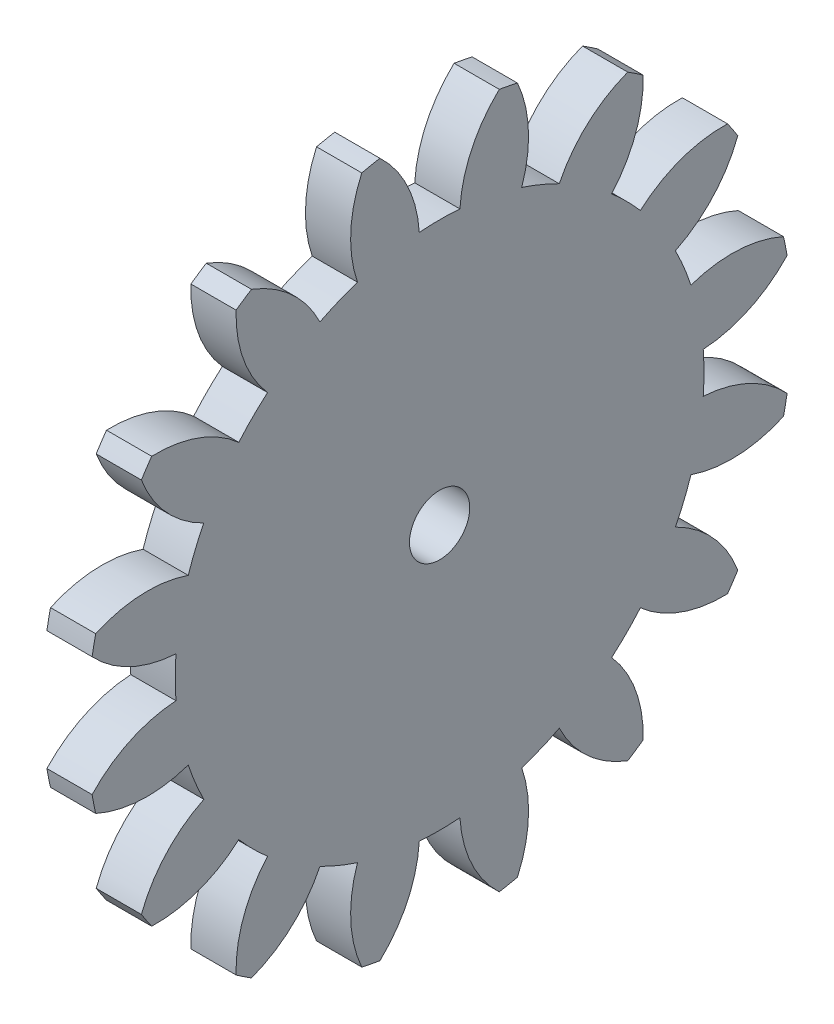
SolidWorks part; units mm, degrees
ref_plane "Plane1" through (0, 0, 0) normal (0, 0, 1) x (1, 0, 0)
ref_plane "Plane2" through (0, 0, 0) normal (0, 1, 0) x (1, 0, 0)
ref_plane "Plane3" through (0, 0, 0) normal (1, 0, 0) x (0, 0, -1)
sketch "HoldingSke" plane through (0, 0, 0) normal (0, 1, 0) x (1, 0, 0)
  line L0 (0, 0) -> (0.7394, -0.212)
  line L1 (-15, 0) -> (100, 0) construction
  line L2 (0, 0) -> (-2.1039, 2.3779)
  line L3 (0, 0) -> (-11.863, 4.5341)
  line L4 (0, 0) -> (8.3015, 2.3804)
  line L5 (0, 0) -> (-46.8476, -17.4728)
  line L6 (0, 0) -> (-1.2434, -0.839)
  line L7 (-2.1039, 2.3779) -> (8.6586, 51.2059)
  line L8 (-76.2, 54.61) -> (-75.9, 54.61)
  line L9 (-71.009, 38.7566) -> (-53.1078, 45.2721)
  line L10 (-76.2, 71.12) -> (104.1128, 71.12)
  line L11 (0, 0) -> (-1.5, 0)
  line L12 (-76.2, 101.6) -> (-76.155, 101.6)
  line L13 (24.9733, 27.94) -> (52.9518, 28.4284)
  line L14 (24.9733, 27.94) -> (24.9743, 27.94)
  line L15 (24.9733, 27.94) -> (100.4006, 29.5858)
  line L16 (-63.627, -1.3) -> (-12.827, -1.3)
  circle A0 centre (0, 0) radius 1
  circle A1 centre (0, 0) radius 8.774
  circle A2 centre (0, 0) radius 37.5
  circle A3 centre (0, 0) radius 1
  dimension "MHD" = 17.548
  dimension "Hub_dia" = 75
  dimension "Bore" = 2
  dimension "MBD" = 2
  dimension "Num_teeth" = 16
  dimension "Pitch" = 0.7692
  dimension "Overall_len" = 50
  dimension "Show_teeth" = 16
  dimension "Thickness" = 1.5
  dimension "OAL" = 50.0001
  dimension "T_dim" = 0.3
  dimension "Ap" = 20
  dimension "H" = 19.05
  dimension "Pitch_radius" = 180.3128
  dimension "Width" = 1.5
  dimension "Backlash" = 0.045
  dimension "Addendum_fac" = 1
  dimension "Dedendum_fac" = 1.25
  dimension "Clearance_fac" = 0.25
  dimension "Dedendum_add" = 0.001
  dimension "Module" = 1.3
sketch "BasProSke" plane through (0, 0, 0) normal (0, 1, 0) x (1, 0, 0)
  line L0 (-10, 0) -> (60, 0) construction
  line L1 (0, 0) -> (0, 11.7)
  line L2 (0, 0) -> (1.5, 0)
  line L3 (1.5, 0) -> (1.5, 11.7)
  line L4 (1.5, 11.7) -> (0, 11.7)
  dimension "Thickness" = 1.5
  dimension "Diameter" = 23.4
revolve "Base-Revolve" add sketch "BasProSke" angle 360 about L0
sketch "TooCutSke" plane through (0, 0, 0) normal (1, 0, 0) x (0, 0, -1)
  line L1 (0, 0) -> (0, 107) construction
  line L2 (0, 0) -> (-1.0981, 10.3419) construction
  line L3 (0, 0) -> (-4.0412, 20.3167) construction
  line L4 (-1.0981, 10.3419) -> (-2.0206, 10.1584) construction
  arc A0 (0.6744, 8.748) -> (-0.6744, 8.748) centre (0, 0) ccw
  arc A1 (2.0037, 11.5529) -> (-2.0037, 11.5529) centre (0, 0) ccw
  circle A2 centre (0, 0) radius 10.4 construction
  circle A3 centre (0, 0) radius 9.7728 construction
  arc A4 (-0.6744, 8.748) -> (-2.0037, 11.5529) centre (-4.8269, 8.4976) ccw
  arc A5 (2.0037, 11.5529) -> (0.6744, 8.748) centre (4.8269, 8.4976) ccw
  dimension "Root_dia" = 17.548
  dimension "Overcut_dia" = 23.4508
  dimension "Pitch_dia" = 20.8
  dimension "Base_dia" = 19.5456
  dimension "Flank_rad" = 4.16
  dimension "Half_ang" = 11.25
  dimension "Half_CT" = 0.9406
extrude "ToothCut" cut sketch "TooCutSke" along normal through all
fillet "Breaks" [suppressed] radius 0.026
fillet "RootFillets" [suppressed] radius 0.326
pattern_circular "TeethCuts" count 16 every 22.5 about axis through (-10, 0, 0) along (1, 0, 0) of "ToothCut", "RootFillets", "Breaks"
sketch "HubNeaOneSke" plane through (0, 0, 0) normal (-1, 0, 0) x (0, 0, 1)
  circle A0 centre (0, 0) radius 8.774
  dimension "Diameter" = 17.548
extrude "HubNearOne" [suppressed] add sketch "HubNeaOneSke" along normal blind 48.5001
sketch "HubNeaBotSke" plane through (0, 0, 0) normal (-1, 0, 0) x (0, 0, 1)
  circle A0 centre (0, 0) radius 8.774
  dimension "Diameter" = 17.548
extrude "HubNearBoth" [suppressed] add sketch "HubNeaBotSke" along normal blind 24.25
ref_plane "FarPln" through (1.5, 0, 0) normal (1, 0, 0) x (0, 0, -1)
sketch "HubFarSke" plane through (1.5, 0, 0) normal (1, 0, 0) x (0, 0, -1)
  circle A0 centre (0, 0) radius 8.774
  dimension "Diameter" = 17.548
extrude "HubFar" [suppressed] add sketch "HubFarSke" along normal blind 24.25
sketch "BorSke" plane through (0, 0, 0) normal (1, 0, 0) x (0, 0, -1)
  circle A0 centre (0, 0) radius 1
  dimension "Diameter" = 2
extrude "Bore" cut sketch "BorSke" along normal mid plane 100.0001
sketch "KeySke" plane through (0, 0, 0) normal (1, 0, 0) x (0, 0, -1)
  line L0 (-0.4, 0) -> (-0.4, 1.3)
  line L1 (-0.4, 1.3) -> (0.4, 1.3)
  line L2 (0.4, 1.3) -> (0.4, 0)
  line L3 (0, 0) -> (0, 34) construction
  line L4 (-0.4, 0) -> (0.4, 0)
  dimension "Offset" = 1.3
  dimension "Width" = 0.8
extrude "Keyway" [suppressed] cut sketch "KeySke" along normal mid plane 100.0001
pattern_circular "Keyway2" [suppressed] count 2 every 90 about axis through (-10, 0, 0) along (1, 0, 0)
equation "' \"Module@HoldingSke\" = 6.35"
equation "' \"Num_teeth@HoldingSke\" = 12"
equation "' \"Ap@HoldingSke\" =  20"
equation "' \"Ap@HoldingSke\" = 20"
equation "' \"Width@HoldingSke\" = 0.5 * 25.4"
equation "' \"Hub_dia@HoldingSke\"= 1 * 25.4"
equation "' \"Hub_dia@HoldingSke\" = 1 * 25.4"
equation "' \"Overall_len@HoldingSke\" = 1.0 * 25.4"
equation "' \"Bore@HoldingSke\" = 0.75 * 25.4"
equation "' \"T_dim@HoldingSke\" = 0.1 * 25.4"
equation "' \"Width@KeySke\" = 0.25 * 25.4"
equation "' \"Show_teeth@HoldingSke\" = 13"
equation "' \"Backlash@HoldingSke\" = 0.009 * 25.4"
equation "' \"Addendum_fac@HoldingSke\" = 1.0"
equation "' \"Dedendum_fac@HoldingSke\" = 1.25"
equation "' \"Dedendum_add@HoldingSke\" = 0.00005 * 25.4"
equation "' \"Clearance_fac@HoldingSke\" = 0.25"
equation "\"Pitch@HoldingSke\" = 1 / \"Module@HoldingSke\""
equation "\"Overcut_dia@TooCutSke\" = (\"Num_teeth@HoldingSke\" + 2 * \"Addendum_fac@HoldingSke\") / \"Pitch@HoldingSke\" + 0.002 * 25.4"
equation "\"Pitch_dia@TooCutSke\" = \"Num_teeth@HoldingSke\" / \"Pitch@HoldingSke\""
equation "\"Base_dia@TooCutSke\" = \"Num_teeth@HoldingSke\" / \"Pitch@HoldingSke\" * cos((\"Ap@HoldingSke\"  * 3.14159265 / 180))"
equation "\"Root_dia@TooCutSke\" = (\"Num_teeth@HoldingSke\" + 2) / \"Pitch@HoldingSke\" - 2 * (\"Addendum_fac@HoldingSke\" + \"Dedendum_fac@HoldingSke\") / \"Pitch@HoldingSke\" - \"Dedendum_add@HoldingSke\" * 2"
equation "\"Half_ang@TooCutSke\" = 180 / \"Num_teeth@HoldingSke\""
equation "\"Half_CT@TooCutSke\" = \"Num_teeth@HoldingSke\" / \"Pitch@HoldingSke\" * sin((3.14159265 / 2 / \"Num_teeth@HoldingSke\")) / 2 - 7 * \"Backlash@HoldingSke\" / 4"
equation "\"Flank_rad@TooCutSke\" = \"Num_teeth@HoldingSke\" / \"Pitch@HoldingSke\" / 5"
equation "\"Radius@RootFillets\" = \"Clearance_fac@HoldingSke\" / \"Pitch@HoldingSke\" + \"Dedendum_add@HoldingSke\""
equation "\"Break_rad@Breaks\" = 0.02 / \"Pitch@HoldingSke\""
equation "\"Thickness@HoldingSke\" = \"Width@HoldingSke\""
equation "\"OAL@HoldingSke\" = \"Thickness@HoldingSke\""
equation "\"MHD@HoldingSke\" = (\"Num_teeth@HoldingSke\" + 2) / \"Pitch@HoldingSke\" - 2 * (\"Addendum_fac@HoldingSke\" + \"Dedendum_fac@HoldingSke\")  / \"Pitch@HoldingSke\" - \"Dedendum_add@HoldingSke\" * 2"
equation "\"MBD@HoldingSke\" = (\"Num_teeth@HoldingSke\" + 2) / \"Pitch@HoldingSke\" - 2 * (\"Addendum_fac@HoldingSke\" + \"Dedendum_fac@HoldingSke\")  / \"Pitch@HoldingSke\" - \"Dedendum_add@HoldingSke\" * 2 - 0.002 * 25.4"
equation "\"MHD@HoldingSke\" = ((sgn( \"MHD@HoldingSke\" - \"Hub_dia@HoldingSke\" )-1)*( \"MHD@HoldingSke\" - \"Hub_dia@HoldingSke\" ))/-2+ \"Hub_dia@HoldingSke\""
equation "\"MBD@HoldingSke\" = ((sgn( \"MBD@HoldingSke\" - \"Bore@HoldingSke\" )-1)*( \"MBD@HoldingSke\" - \"Bore@HoldingSke\" ))/-2+ \"Bore@HoldingSke\""
equation "\"OAL@HoldingSke\" = ((sgn( \"OAL@HoldingSke\" - \"Overall_len@HoldingSke\" )+1)*( \"OAL@HoldingSke\" - \"Overall_len@HoldingSke\" ))/2 + \"Overall_len@HoldingSke\" + 0.000002 * 25.4"
equation "\"Num_teeth@TeethCuts\" = int( \"Show_teeth@HoldingSke\" ) + 1"
equation "\"Num_teeth@TeethCuts\" = ((sgn( \"Num_teeth@TeethCuts\" - \"Num_teeth@HoldingSke\" )-1)*( \"Num_teeth@TeethCuts\" - \"Num_teeth@HoldingSke\" ))/-2+ \"Num_teeth@HoldingSke\""
equation "\"Num_teeth@TeethCuts\" = ((sgn( \"Num_teeth@TeethCuts\" - 2.0)+1)*( \"Num_teeth@TeethCuts\" - 2.0))/2 +2.0"
equation "\"Angle@TeethCuts\" = 360.0 / \"Num_teeth@HoldingSke\""
equation "\"Diameter@BasProSke\" = (\"Num_teeth@HoldingSke\" + 2 * \"Addendum_fac@HoldingSke\") / \"Pitch@HoldingSke\""
equation "\"Thickness@BasProSke\"  = \"Thickness@HoldingSke\""
equation "' \"Fillet_rad@BasProSke\" =  \"Thickness@HoldingSke\" * 0.05"
equation "' \"Fillet_rad@BasProSke\" = \"Thickness@HoldingSke\" * 0.05"
equation "\"MHD@HoldingSke\" = ((sgn( \"MHD@HoldingSke\" - \"Root_dia@TooCutSke\" )-1)*( \"MHD@HoldingSke\" - \"Root_dia@TooCutSke\" ))/-2+ \"Root_dia@TooCutSke\""
equation "\"Diameter@HubNeaOneSke\" = \"MHD@HoldingSke\""
equation "\"Length@HubNearOne\" = \"OAL@HoldingSke\" - \"Thickness@BasProSke\""
equation "\"Diameter@HubNeaBotSke\" = \"MHD@HoldingSke\""
equation "\"Length@HubNearBoth\" = ( \"OAL@HoldingSke\" - \"Thickness@BasProSke\" ) / 2.0"
equation "\"Thickness@FarPln\" = \"Thickness@BasProSke\""
equation "\"Diameter@HubFarSke\" = \"MHD@HoldingSke\""
equation "\"Length@HubFar\" = ( \"OAL@HoldingSke\" - \"Thickness@BasProSke\" ) / 2.0"
equation "\"Diameter@BorSke\" = \"MBD@HoldingSke\""
equation "\"D1@Bore\" = \"OAL@HoldingSke\" * 2.0"
equation "\"D1@Keyway\" = \"OAL@HoldingSke\" * 2.0"
equation "\"Offset@KeySke\" = \"T_dim@HoldingSke\" + \"MBD@HoldingSke\" / 2.0"
